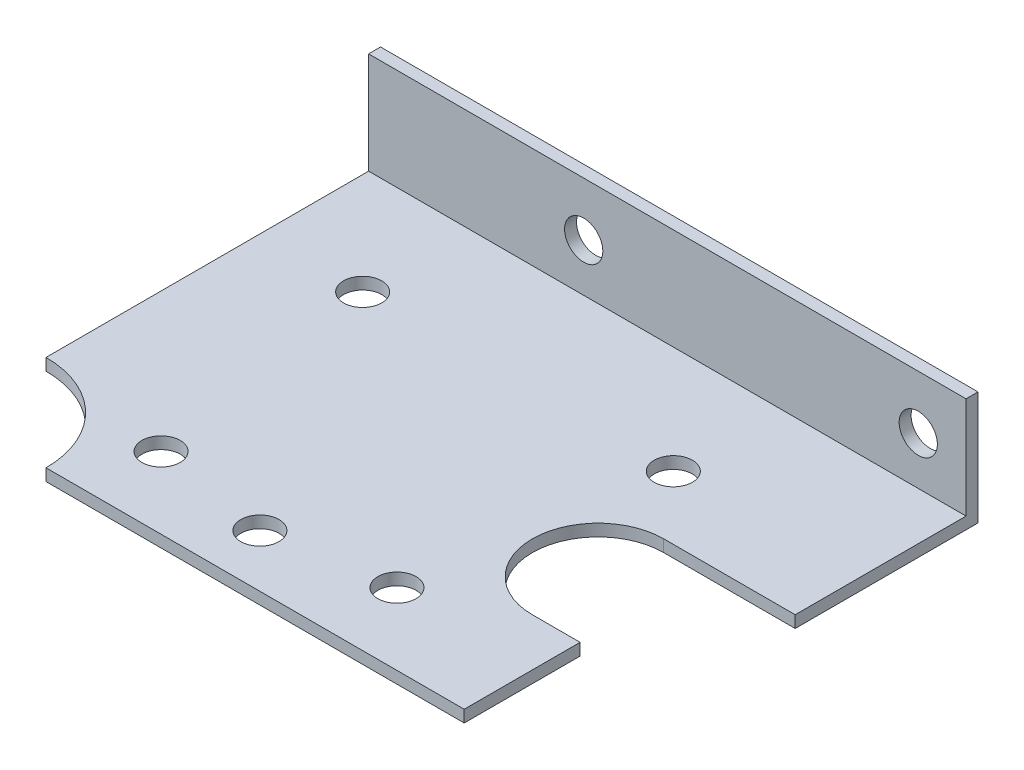
SolidWorks part; units mm, degrees
ref_plane "前视基准面" through (0, 0, 0) normal (0, 0, 1) x (1, 0, 0)
ref_plane "上视基准面" through (0, 0, 0) normal (0, 1, 0) x (1, 0, 0)
ref_plane "右视基准面" through (0, 0, 0) normal (1, 0, 0) x (0, 0, -1)
sketch "草图1" plane through (0, 0, 0) normal (0, 1, 0) x (1, 0, 0)
  line L0 (21.5, 35) -> (21.5, 0) construction
  line L1 (8, 0) -> (43, 0)
  line L2 (0, 8) -> (0, 36)
  line L3 (0, 36) -> (50, 36)
  line L4 (43, 0) -> (43, 9.7)
  line L5 (78.2626, 15.2) -> (-19.7659, 15.2) construction
  line L6 (39, 20.7) -> (50, 20.7)
  line L7 (39, 9.7) -> (43, 9.7)
  line L8 (50, 20.7) -> (50, 36)
  circle A0 centre (8.5, 26) radius 1.6
  circle A2 centre (21.5, 4.4) radius 1.6
  circle A3 centre (34.5, 26) radius 1.6
  arc A4 (39, 9.7) -> (39, 20.7) centre (39, 15.2) cw
  circle A5 centre (31.3712, 6) radius 1.6
  circle A6 centre (11.6288, 6) radius 1.6
  arc A7 (8, 0) -> (0, 8) centre (0, 0) ccw
  dimension "D3" = 3.2
  dimension "D4" = 26
  dimension "D5" = 21.6
  dimension "D6" = 10
  dimension "D8" = 5.5
  dimension "D10" = 3.2
  dimension "D11" = 20
  dimension "D13" = 21.5
  dimension "D9" = 4
  dimension "D16" = 20
  dimension "D17" = 10.8
  dimension "D18" = 8
  dimension "D1" = 50
  dimension "D2" = 36
  dimension "D7" = 10.8
  dimension "D12" = 10
  dimension "D14" = 43
  dimension "D15" = 11
extrude "凸台-拉伸1" add sketch "草图1" along normal blind 1
sketch "草图2" plane through (0, 1, 0) normal (0, 1, 0) x (1, 0, 0)
  line L0 (50, 20.7) -> (50, 36) construction
  line L1 (0, 36) -> (50, 36)
  line L2 (0, 36) -> (0, 35)
  line L3 (0, 35) -> (50, 35)
  line L4 (50, 36) -> (50, 35)
  dimension "D1" = 1
extrude "凸台-拉伸2" add sketch "草图2" along normal blind 8.5
sketch "草图3" plane through (0, 0, -35) normal (0, 0, 1) x (1, 0, 0)
  line L0 (0, 1) -> (50, 1) construction
  line L1 (50, 9.5) -> (50, 1) construction
  circle A0 centre (46, 5) radius 1.6
  circle A1 centre (18, 5) radius 1.6
  dimension "D1" = 4
  dimension "D2" = 4
  dimension "D3" = 3.2
  dimension "D4" = 3.2
  dimension "D5" = 28
extrude "切除-拉伸1" cut sketch "草图3" against normal blind 10
